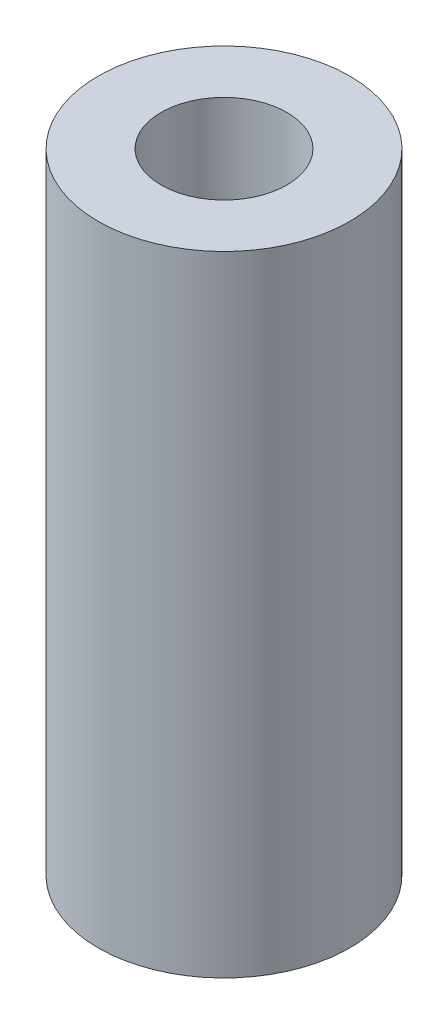
SolidWorks part; units mm, degrees
ref_plane "Alzado" through (0, 0, 0) normal (0, 0, 1) x (1, 0, 0)
ref_plane "Planta" through (0, 0, 0) normal (0, 1, 0) x (1, 0, 0)
ref_plane "Vista lateral" through (0, 0, 0) normal (1, 0, 0) x (0, 0, -1)
sketch "Croquis1" plane through (0, 0, 0) normal (0, 1, 0) x (1, 0, 0)
  circle A0 centre (-11.6487, -0.3929) radius 2
  circle A1 centre (-11.6487, -0.3929) radius 4
  dimension "D1" = 4
  dimension "D2" = 2
extrude "Saliente-Extruir1" add sketch "Croquis1" along normal blind 20
